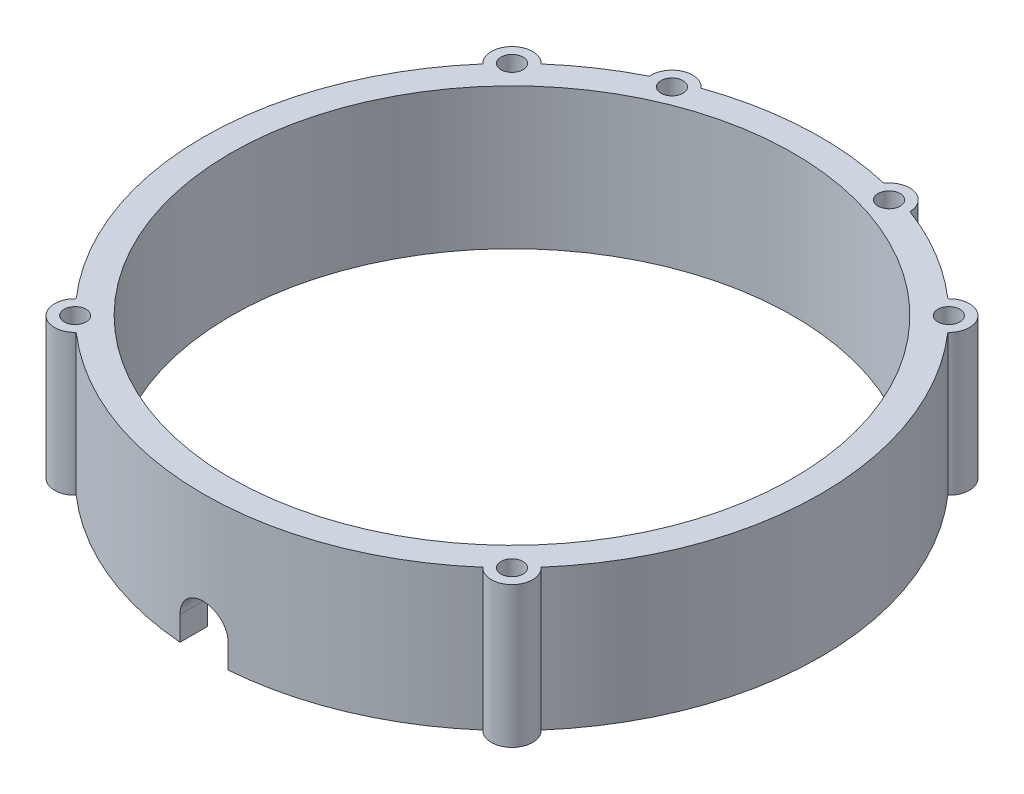
SolidWorks part; units mm, degrees
ref_plane "前视基准面" through (0, 0, 0) normal (0, 0, 1) x (1, 0, 0)
ref_plane "上视基准面" through (0, 0, 0) normal (0, 1, 0) x (1, 0, 0)
ref_plane "右视基准面" through (0, 0, 0) normal (1, 0, 0) x (0, 0, -1)
sketch "草图1" plane through (0, 0, 0) normal (0, 1, 0) x (1, 0, 0)
  line L0 (0, 0) -> (0, 46.9) construction
  line L4 (0, 0) -> (13.7122, 44.8507) construction
  line L6 (0, 0) -> (-17.1531, 40.4102) construction
  circle A0 centre (0, 0) radius 40.9
  circle A7 centre (0, 0) radius 46.9
  circle A13 centre (0, 0) radius 43.9 construction
  circle A14 centre (12.8351, 41.9818) radius 1.6
  circle A15 centre (-17.1531, 40.4102) radius 1.6
  dimension "D1" = 81.8
  dimension "D2" = 6
  dimension "D3" = 17
  dimension "D4" = 3
  dimension "D5" = 3.2
  dimension "D6" = 40
extrude "凸台-拉伸1" add sketch "草图1" along normal blind 20.5
sketch "草图2" plane through (0, 20.5, 0) normal (0, 1, 0) x (1, 0, 0)
  line L0 (0, 0) -> (0, 44.9) construction
  line L1 (0, 0) -> (31.7491, 31.7491) construction
  circle A1 centre (0, 0) radius 44.9 construction
  circle A2 centre (31.7491, 31.7491) radius 3
  circle A3 centre (31.7491, -31.7491) radius 3
  circle A4 centre (-31.7491, -31.7491) radius 3
  circle A5 centre (-31.7491, 31.7491) radius 3
  circle A6 centre (0, 0) radius 46.9 construction
  dimension "D1" = 89.8
  dimension "D3" = 6
  dimension "D2" = 45
  dimension "D4" = 4
extrude "凸台-拉伸2" add sketch "草图2" against normal up to surface (20.5 mm away) up to face at (0, 0, 46.9)
sketch "草图3" plane through (0, 20.5, 0) normal (0, 1, 0) x (1, 0, 0)
  circle A0 centre (0, 0) radius 44.9 construction
  circle A1 centre (-31.7491, 31.7491) radius 1.6
  circle A2 centre (-31.7491, -31.7491) radius 1.6
  circle A3 centre (31.7491, -31.7491) radius 1.6
  circle A4 centre (31.7491, 31.7491) radius 1.6
  dimension "D1" = 3.2
extrude "切除-拉伸1" cut sketch "草图3" against normal blind 25
sketch "草图4" plane through (0, 20.5, 0) normal (0, 1, 0) x (1, 0, 0)
  arc A0 (-34.7394, 31.5084) -> (-34.7394, -31.5084) centre (0, 0) ccw
  arc A1 (-33.7984, 29.5581) -> (-33.7984, -29.5581) centre (0, 0) ccw
  arc A2 (-34.7394, 31.5084) -> (-33.7984, 29.5581) centre (-31.7491, 31.7491) ccw
  arc A3 (31.5084, 34.7394) -> (29.5581, 33.7984) centre (31.7491, 31.7491) ccw
  arc A4 (34.7394, -31.5084) -> (33.7984, -29.5581) centre (31.7491, -31.7491) ccw
  arc A5 (-33.7984, -29.5581) -> (-34.7394, -31.5084) centre (-31.7491, -31.7491) ccw
  arc A6 (-29.5581, 33.7984) -> (-31.5084, 34.7394) centre (-31.7491, 31.7491) ccw
  arc A7 (31.5084, 34.7394) -> (-31.5084, 34.7394) centre (0, 0) ccw
  arc A8 (29.5581, 33.7984) -> (15.8349, 42.0151) centre (0, 0) ccw
  arc A9 (33.7984, 29.5581) -> (34.7394, 31.5084) centre (31.7491, 31.7491) ccw
  arc A10 (34.7394, -31.5084) -> (34.7394, 31.5084) centre (0, 0) ccw
  arc A11 (33.7984, -29.5581) -> (33.7984, 29.5581) centre (0, 0) ccw
  arc A12 (29.5581, -33.7984) -> (31.5084, -34.7394) centre (31.7491, -31.7491) ccw
  arc A13 (-29.5581, -33.7984) -> (29.5581, -33.7984) centre (0, 0) ccw
  arc A14 (-31.5084, -34.7394) -> (31.5084, -34.7394) centre (0, 0) ccw
  arc A15 (-31.5084, -34.7394) -> (-29.5581, -33.7984) centre (-31.7491, -31.7491) ccw
  arc A16 (-14.8765, 42.3639) -> (-20.14, 40.1297) centre (-17.1531, 40.4102) ccw
  arc A17 (15.8349, 42.0151) -> (10.3668, 43.6868) centre (12.8351, 41.9818) ccw
  arc A18 (-20.14, 40.1297) -> (-29.5581, 33.7984) centre (0, 0) ccw
  arc A19 (10.3668, 43.6868) -> (-14.8765, 42.3639) centre (0, 0) ccw
  arc M8 (31.5084, 34.7394) -> (-31.5084, 34.7394) centre (0, 0) ccw
  arc M10 (-34.7394, 31.5084) -> (-34.7394, -31.5084) centre (0, 0) ccw
  arc M12 (-31.5084, -34.7394) -> (31.5084, -34.7394) centre (0, 0) ccw
  arc M14 (34.7394, -31.5084) -> (34.7394, 31.5084) centre (0, 0) ccw
extrude "切除-拉伸2" cut sketch "草图4" against normal blind 25 contours A18 A16 A7 A6 | A19 A17 A7 A16 | A17 A8 A3 M8 | A11 A4 A9 M14 | A5 A1 A2 M10 | A15 A12 A13 M12
sketch "草图5" plane through (0, 0, 0) normal (0, 0, 1) x (1, 0, 0)
  line L0 (0, 0) -> (0, 3.5) construction
  line L1 (-3.5, 3.5) -> (-3.5, 0)
  line L2 (-3.5, 0) -> (3.5, 0)
  line L3 (3.5, 0) -> (3.5, 3.5)
  arc A0 (3.5, 3.5) -> (-3.5, 3.5) centre (0, 3.5) ccw
  dimension "D1" = 3.5
extrude "切除-拉伸3" cut sketch "草图5" along normal through all
